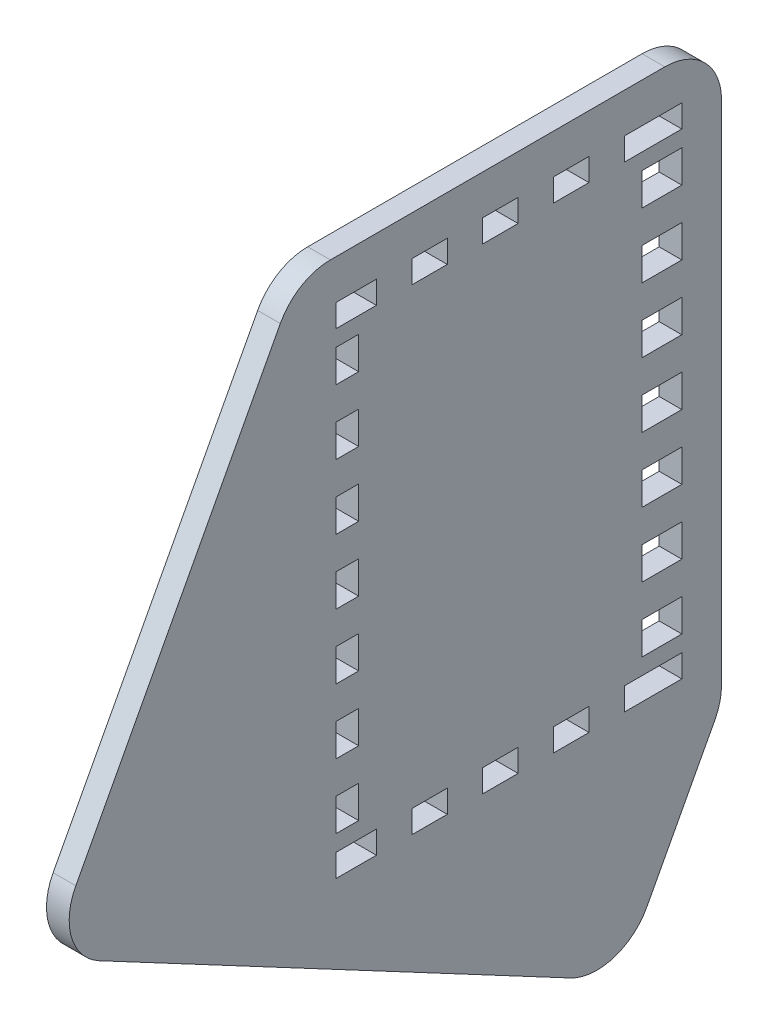
SolidWorks part; units mm, degrees
ref_plane "Piano frontale" through (0, 0, 0) normal (0, 0, 1) x (1, 0, 0)
ref_plane "Piano superiore" through (0, 0, 0) normal (0, 1, 0) x (1, 0, 0)
ref_plane "Piano destro" through (0, 0, 0) normal (1, 0, 0) x (0, 0, -1)
sketch "Schizzo1" plane through (0, 0, 0) normal (1, 0, 0) x (0, 0, -1)
  line L1 (0, 0) -> (50, 0)
  line L2 (0, 0) -> (0, 80)
  line L3 (0, 80) -> (50, 80)
  line L4 (50, 0) -> (50, 80)
  dimension "D1" = 80
  dimension "D2" = 50
extrude "Estrusione-Estrusione1" add sketch "Schizzo1" along normal blind 4
sketch "Schizzo2" plane through (4, 0, 0) normal (1, 0, 0) x (0, 0, -1)
  line L0 (0, 80) -> (0, 0) construction
  line L1 (0, 77.1429) -> (-4, 77.1429)
  line L2 (0, 77.1429) -> (0, 80)
  line L3 (0, 80) -> (-4, 80)
  line L4 (-4, 77.1429) -> (-4, 80)
  line L6 (50, 80) -> (57, 80)
  line L7 (50, 80) -> (50, 77.1429)
  line L8 (50, 77.1429) -> (57, 77.1429)
  line L9 (57, 80) -> (57, 77.1429)
  line L10 (50, 0) -> (57, 0)
  line L11 (50, 0) -> (50, 2.8571)
  line L12 (50, 2.8571) -> (57, 2.8571)
  line L13 (57, 0) -> (57, 2.8571)
  line L14 (0, 0) -> (-4, 0)
  line L15 (0, 0) -> (0, 2.8571)
  line L16 (0, 2.8571) -> (-4, 2.8571)
  line L17 (-4, 0) -> (-4, 2.8571)
  dimension "D1" = 4
  dimension "D2" = 7
  dimension "D3" = 2.8571
  dimension "D4" = 2.8571
extrude "Estrusione-Estrusione2" add sketch "Schizzo2" against normal blind 4
sketch "Schizzo3" plane through (4, 0, 0) normal (1, 0, 0) x (0, 0, -1)
  line L0 (0, 77.1429) -> (0, 2.8571) construction
  line L1 (0, 71.4286) -> (-4, 71.4286)
  line L2 (0, 71.4286) -> (0, 65.7143)
  line L3 (0, 65.7143) -> (-4, 65.7143)
  line L4 (-4, 71.4286) -> (-4, 65.7143)
  line L5 (50, 2.8571) -> (50, 77.1429) construction
  line L6 (50, 71.4286) -> (57, 71.4286)
  line L7 (50, 71.4286) -> (50, 65.7143)
  line L8 (50, 65.7143) -> (57, 65.7143)
  line L9 (57, 71.4286) -> (57, 65.7143)
  line L10 (-4, 77.1429) -> (0, 77.1429) construction
  line L11 (-4, 80) -> (-4, 77.1429) construction
  line L12 (57, 77.1429) -> (57, 80) construction
  dimension "D1" = 5.7143
  dimension "D2" = 5.7143
extrude "Estrusione-Estrusione3" add sketch "Schizzo3" against normal blind 4
pattern_linear "Ripetizione a L1" count 6 spacing 11.4286 along (0, -1, 0) of "Estrusione-Estrusione3"
sketch "Schizzo4" plane through (4, 0, 0) normal (1, 0, 0) x (0, 0, -1)
  line L0 (57, 80) -> (-4, 80) construction
  line L1 (3.125, 80) -> (9.375, 80)
  line L2 (3.125, 80) -> (3.125, 84)
  line L3 (3.125, 84) -> (9.375, 84)
  line L4 (9.375, 80) -> (9.375, 84)
  line L5 (-4, 0) -> (57, 0) construction
  line L6 (3.125, 0) -> (9.375, 0)
  line L7 (3.125, 0) -> (3.125, -4)
  line L8 (3.125, -4) -> (9.375, -4)
  line L9 (9.375, 0) -> (9.375, -4)
  line L10 (0, 77.1429) -> (0, 71.4286) construction
  point P14 (6.25, 0)
  dimension "D1" = 3.125
  dimension "D2" = 6.25
  dimension "D3" = 4
  dimension "D4" = 4
extrude "Estrusione-Estrusione4" add sketch "Schizzo4" against normal blind 4
pattern_linear "Ripetizione a L2" count 4 spacing 12.5 along (0, 0, -1) of "Estrusione-Estrusione4"
sketch "Schizzo5" plane through (4, 0, 0) normal (1, 0, 0) x (0, 0, -1)
  line L1 (64, -11) -> (46.1601, -44.552)
  line L2 (46.1601, -44.552) -> (-54.5906, 9.0181)
  line L3 (-54.5906, 9.0181) -> (-11, 91)
  line L7 (-4, 84) -> (-4, -4)
  line L9 (-4, -4) -> (57, -4)
  line L10 (57, -4) -> (57, 84)
  line L11 (57, 84) -> (-4, 84)
  line L12 (-11, 91) -> (64, 91)
  line L13 (64, 91) -> (64, -11)
  line L14 (-4, 71.4286) -> (-4, 65.7143) construction
  line L15 (9.375, 84) -> (3.125, 84) construction
  line L16 (28.125, -4) -> (34.375, -4) construction
  line L17 (57, 0) -> (57, 2.8571) construction
  dimension "D1" = 62
  dimension "D2" = 7
  dimension "D3" = 7
  dimension "D4" = 38
  dimension "D5" = 7
  dimension "D6" = 7
extrude "Estrusione-Estrusione5" add sketch "Schizzo5" against normal blind 4
fillet "Raccordo1" radius 10 2 edges at (2, -44.552, -46.1601) (2, 9.0181, 54.5906)
fillet "Raccordo2" radius 10 3 edges at (2, -11, -64) (2, 91, -64) (2, 91, 11)
equation "\"WFront\"= 140mm"
equation "\"HFront\"= 80mm"
equation "\"DFront\"= 4mm"
equation "\"WLeft\"= 50mm"
equation "\"HLeft\"= 80mm"
equation "\"DLeft\"= 4mm"
equation "\"WTop\"= 140mm"
equation "\"HTop\"= 50mm"
equation "\"DTop\"= 4mm"
equation "\"N_Denti_W\"= 10"
equation "\"N_Denti_H\"= 7"
equation "\"N_Denti_D\"= 4"
equation "\"HDistDenti\"= \"HFront\" / \"N_Denti_H\""
equation "\"WDistDenti\"= \"WFront\" / \"N_Denti_W\""
equation "\"DDistDenti\"= \"WLeft\" / \"N_Denti_D\""
equation "\"HDenti\"= \"HDistDenti\" / 2"
equation "\"WDenti\"= \"WDistDenti\" / 2"
equation "\"DDenti\"= \"DDistDenti\" / 2"
equation "\"WDisplay\"= 95mm"
equation "\"HDisplay\"= 61mm"
equation "\"CEnc\"= 7mm"
equation "\"Display_to_Enc_W\"= 11.5 + \"CEnc\" / 2"
equation "\"Display_to_Dx\"= 32mm"
equation "\"Display_to_Top\"= 10mm"
equation "\"Display_to_Enc_H\"= 24 + \"CEnc\" / 2"
equation "\"D1@Schizzo1\"=\"HLeft\""
equation "\"D2@Schizzo1\"=\"WLeft\""
equation "\"D1@Estrusione-Estrusione1\"=\"DLeft\""
equation "\"D1@Schizzo2\"=\"DFront\""
equation "\"D2@Schizzo2\"=\"DFront\"+\"DMask\""
equation "\"D3@Schizzo2\"=\"HDenti\"/2"
equation "\"D4@Schizzo2\"=\"HDenti\"/2 "
equation "\"D1@Estrusione-Estrusione2\"=\"DLeft\""
equation "\"D1@Schizzo3\"=\"HDenti\""
equation "\"D2@Schizzo3\"=\"HDenti\""
equation "\"D1@Estrusione-Estrusione3\"=\"DLeft\""
equation "\"D1@Ripetizione a L1\"=\"N_Denti_H\"-1"
equation "\"D1@Schizzo4\"=\"DDenti\"/2"
equation "\"D2@Schizzo4\"=\"DDenti\""
equation "\"D3@Schizzo4\"=\"DTop\""
equation "\"D4@Schizzo4\"=\"DTop\""
equation "\"D1@Estrusione-Estrusione4\"=\"DLeft\""
equation "\"D3@Ripetizione a L2\"=\"DDistDenti\""
equation "\"D1@Ripetizione a L2\"=\"N_Denti_D\""
equation "\"D1@Estrusione-Estrusione5\"=\"DLeft\""
equation "\"DMask\"= 3mm"
